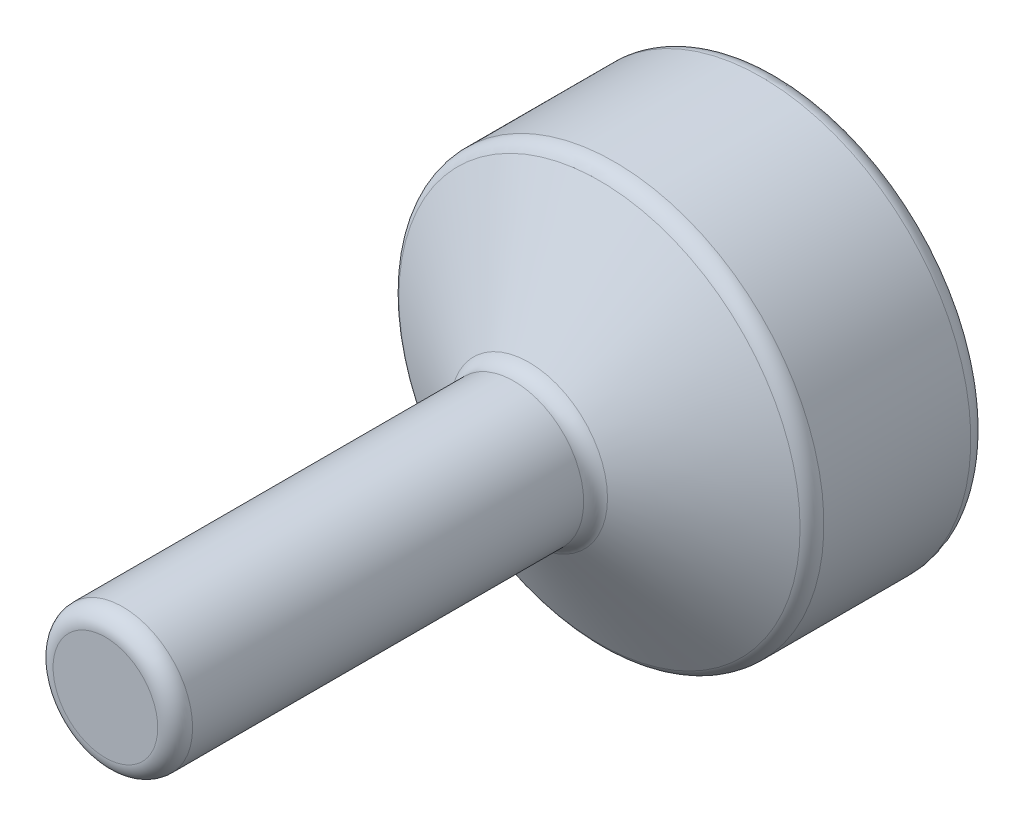
SolidWorks part; units mm, degrees
ref_plane "Front Plane" through (0, 0, 0) normal (0, 0, 1) x (1, 0, 0)
ref_plane "Top Plane" through (0, 0, 0) normal (0, 1, 0) x (1, 0, 0)
ref_plane "Right Plane" through (0, 0, 0) normal (1, 0, 0) x (0, 0, -1)
sketch "Sketch1" plane through (0, 0, 0) normal (0, 1, 0) x (1, 0, 0)
  line L0 (0, 0) -> (3.048, 0)
  line L1 (3.048, 0) -> (3.048, -2.54)
  line L2 (3.048, -2.54) -> (1.016, -3.7132)
  line L3 (1.016, -3.7132) -> (1.016, -9.8092)
  line L4 (1.016, -9.8092) -> (0, -9.8092)
  line L5 (0, -9.8092) -> (0, 0)
  dimension "D1" = 6.096
  dimension "D2" = 2.54
  dimension "D3" = 3.048
  dimension "D4" = 1.016
  dimension "D5" = 120
revolve "Revolve1" add sketch "Sketch1" angle 360 about L5
fillet "Fillet1" radius 0.254 4 edges at (1.016, 0, 9.8092) (3.048, 0, 0) (1.016, 0, 3.7132) (3.048, 0, 2.54)
